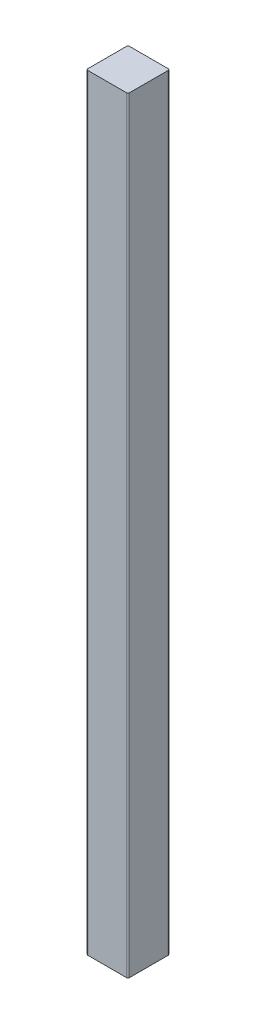
SolidWorks part; units mm, degrees
material "Pine"
ref_plane "Front Plane" through (0, 0, 0) normal (0, 0, 1) x (1, 0, 0)
ref_plane "Top Plane" through (0, 0, 0) normal (0, 1, 0) x (1, 0, 0)
ref_plane "Right Plane" through (0, 0, 0) normal (1, 0, 0) x (0, 0, -1)
sketch "Sketch1" plane through (0, 0, 0) normal (0, 1, 0) x (1, 0, 0)
  line L1 (-44.45, 44.45) -> (44.45, 44.45)
  line L2 (-44.45, 44.45) -> (-44.45, -44.45)
  line L3 (-44.45, -44.45) -> (44.45, -44.45)
  line L4 (44.45, 44.45) -> (44.45, -44.45)
  line L5 (-44.45, 44.45) -> (44.45, -44.45) construction
  line L6 (-44.45, -44.45) -> (44.45, 44.45) construction
  point P0 (0, 0)
  dimension "D1" = 88.9
extrude "Boss-Extrude1" add sketch "Sketch1" along normal blind 1635.125
fillet "Fillet1" radius 3.175 4 edges at (-44.45, 817.5625, 44.45) (-44.45, 817.5625, -44.45) (44.45, 817.5625, -44.45) (44.45, 817.5625, 44.45)
